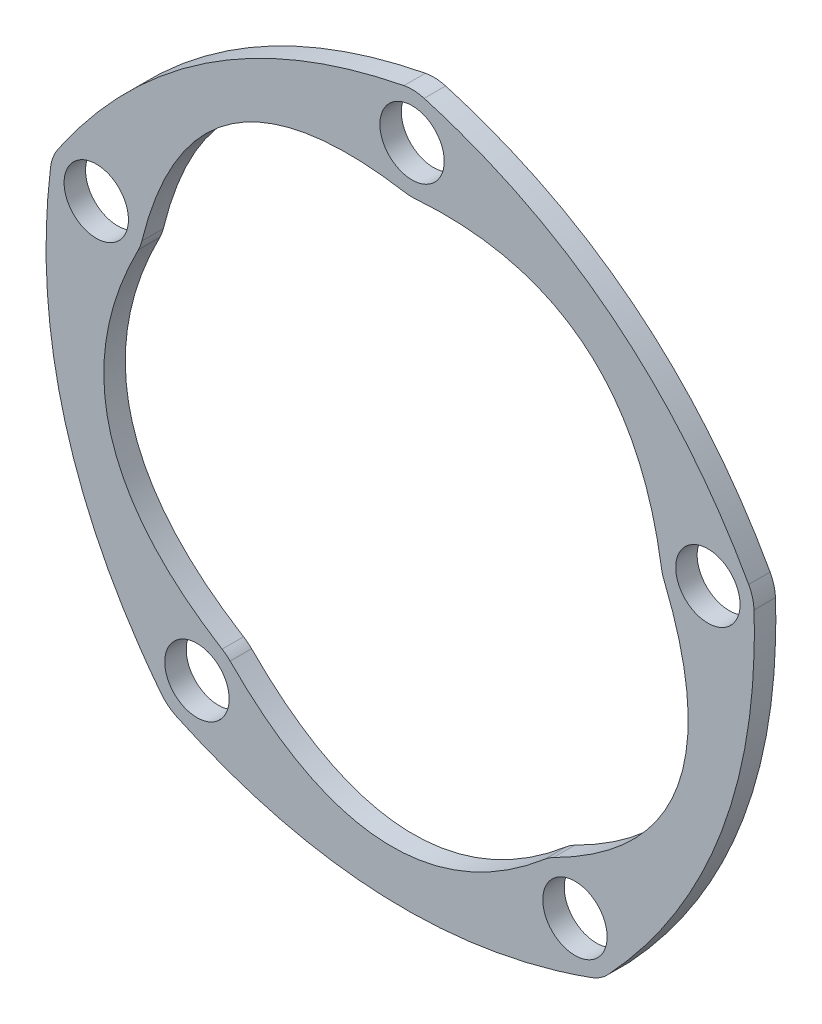
SolidWorks part; units mm, degrees
ref_plane "前视基准面" through (0, 0, 0) normal (0, 0, 1) x (1, 0, 0)
ref_plane "上视基准面" through (0, 0, 0) normal (0, 1, 0) x (1, 0, 0)
ref_plane "右视基准面" through (0, 0, 0) normal (1, 0, 0) x (0, 0, -1)
sketch "草图1" plane through (0, 0, 0) normal (0, 0, 1) x (1, 0, 0)
  line L0 (0, 0) -> (14.555, 18.2541) construction
  line L1 (0, 0) -> (19.9858, 13.1945) construction
  line L2 (0, 0) -> (18.8045, 5.1911) construction
  line L3 (0, 0) -> (0.8621, 19.2262) construction
  circle A2 centre (8.2643, -12.518) radius 1.5
  circle A3 centre (0, 0) radius 15 construction
  circle A9 centre (-9.3515, -11.7281) radius 1.5
  circle A11 centre (-14.0439, 5.2696) radius 1.5
  circle A13 centre (0.6719, 14.9849) radius 1.5
  circle A15 centre (14.4592, 3.9916) radius 1.5
  circle A17 centre (-0.6719, -14.9849) radius 1.5 [skipped]
  circle A18 centre (-14.4592, -3.9916) radius 1.5 [skipped]
  circle A19 centre (-8.2643, 12.518) radius 1.5 [skipped]
  circle A20 centre (9.3515, 11.7281) radius 1.5 [skipped]
  circle A21 centre (14.0439, -5.2696) radius 1.5 [skipped]
  arc A40 (9.0276, -14.53) -> (9.8147, -14.0104) centre (8.3503, -12.6482) ccw
  circle A42 centre (14.4592, 3.9916) radius 2.21 construction
  arc A43 (0.2949, 17.1036) -> (1.2371, 17.0613) centre (0.6789, 15.1408) cw
  arc A44 (-16.1752, 5.5672) -> (-15.8452, 6.4481) centre (-14.1898, 5.3258) cw
  circle A45 centre (0.6719, 14.9849) radius 2.21 construction
  circle A46 centre (9.3515, 11.7281) radius 1.1 construction
  arc A48 (-12.0841, 4.2843) -> (-11.9196, 4.7226) centre (-13.8615, 5.2012) ccw
  arc A49 (-7.8061, -10.1715) -> (-8.1784, -9.8759) centre (-9.2272, -11.5788) ccw
  circle A50 centre (23.154, 13.3715) radius 15 construction
  arc A51 (-11.028, -13.0783) -> (-10.2945, -13.6632) centre (-9.4492, -11.8506) ccw
  arc A52 (6.8652, -10.8299) -> (7.2615, -10.5672) centre (8.1608, -12.3536) cw
  arc A53 (12.2939, 3.6406) -> (12.4213, 3.1826) centre (14.2708, 3.9439) ccw
  arc A54 (16.3595, 5.0028) -> (16.6091, 4.0985) centre (14.6102, 4.0332) cw
  arc A55 (0.3333, 12.8188) -> (0.8154, 12.7972) centre (0.6632, 14.7914) ccw
  spline S0 degree 3 poles (16.3595, 5.0028) (14.6748, 8.0425) (10.4469, 13.1096) (4.5835, 16.0887) (1.2371, 17.0613) knots 0.022009 0.022009 0.022009 0.022009 0.500041 0.977935 0.977935 0.977935 0.977935
  spline S1 degree 3 poles (12.2939, 3.6406) (11.7888, 6.9329) (9.3786, 11.7438) (4.12, 13.0494) (0.8154, 12.7972) knots 0.011651 0.011651 0.011651 0.011651 0.499979 0.988123 0.988123 0.988123 0.988123
  spline S2 degree 3 poles (7.2615, -10.5672) (10.2364, -9.0695) (14.0681, -5.2894) (13.6837, 0.1161) (12.4213, 3.1826) knots 0.011651 0.011651 0.011651 0.011651 0.499963 0.988308 0.988308 0.988308 0.988308
  spline S3 degree 3 poles (9.8147, -14.0104) (12.1882, -11.4588) (15.6929, -5.8936) (16.7225, 0.625) (16.6091, 4.0985) knots 0.022065 0.022065 0.022065 0.022065 0.499959 0.977991 0.977991 0.977991 0.977991
  spline S4 degree 3 poles (-7.8061, -10.1715) (-5.4624, -12.538) (-0.6833, -15.014) (4.3389, -12.9781) (6.8652, -10.8299) knots 0.011648 0.011648 0.011648 0.011648 0.499964 0.988308 0.988308 0.988308 0.988308
  spline S5 degree 3 poles (-10.2945, -13.6632) (-7.1449, -15.1321) (-0.7461, -16.7464) (5.7486, -15.7102) (9.0276, -14.53) knots 0.022009 0.022009 0.022009 0.022009 0.500041 0.977935 0.977935 0.977935 0.977935
  spline S6 degree 3 poles (-12.0841, 4.2843) (-13.6121, 1.3225) (-14.4911, -3.9888) (-11.0021, -8.1368) (-8.1784, -9.8759) knots 0.011463 0.011463 0.011463 0.011463 0.49998 0.988312 0.988312 0.988312 0.988312
  spline S7 degree 3 poles (-16.1752, 5.5672) (-16.5958, 2.1072) (-16.1602, -4.4556) (-13.1614, -10.3348) (-11.028, -13.0783) knots 0.021996 0.021996 0.021996 0.021996 0.499961 0.977991 0.977991 0.977991 0.977991
  spline S8 degree 3 poles (0.3333, 12.8188) (-2.9357, 13.3655) (-8.2911, 12.5358) (-11.1221, 7.9585) (-11.9196, 4.7226) knots 0.011877 0.011877 0.011877 0.011877 0.500004 0.988537 0.988537 0.988537 0.988537
  spline S9 degree 3 poles (0.2949, 17.1036) (-3.1252, 16.4344) (-9.2312, 13.9922) (-13.8954, 9.3242) (-15.8452, 6.4481) knots 0.022065 0.022065 0.022065 0.022065 0.499961 0.977922 0.977922 0.977922 0.977922
  dimension "D1" = 18
  dimension "D2" = 3
  dimension "D3" = 30
  dimension "D4" = 2
  dimension "D6" = 2
  dimension "D7" = 2
  dimension "D5" = 10
extrude "凸台-拉伸1" add sketch "草图1" along normal blind 1
